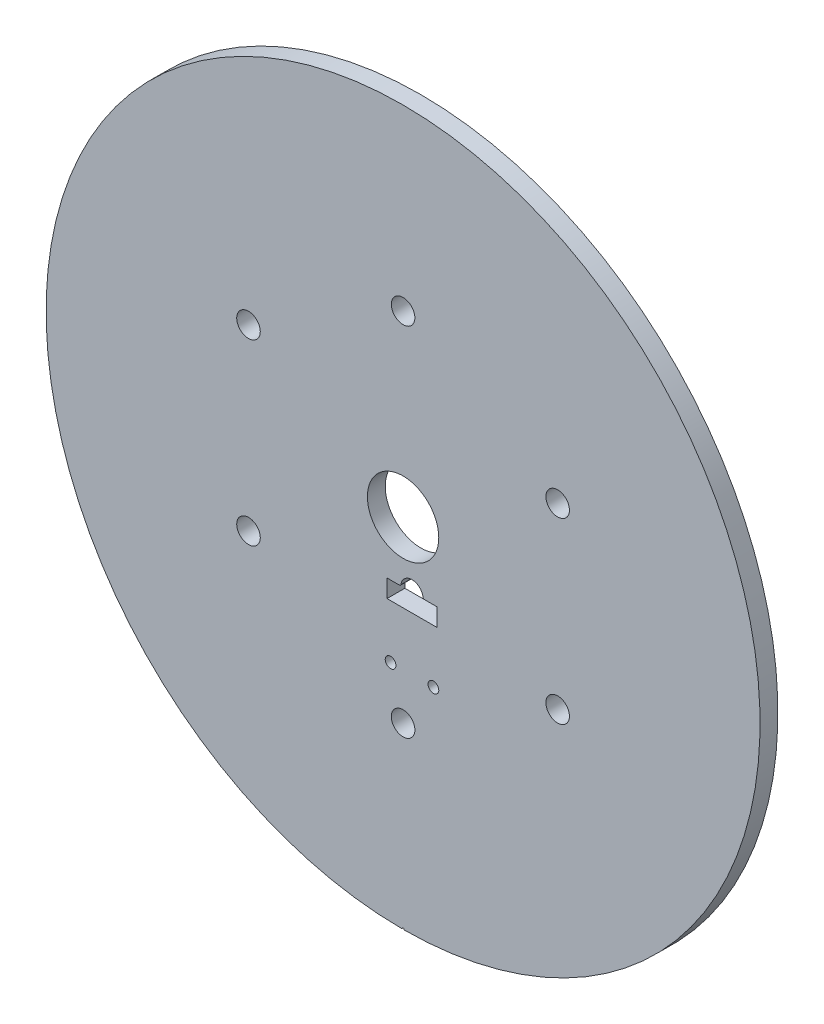
SolidWorks part; units mm, degrees
ref_plane "Front Plane" through (0, 0, 0) normal (0, 0, 1) x (1, 0, 0)
ref_plane "Top Plane" through (0, 0, 0) normal (0, 1, 0) x (1, 0, 0)
ref_plane "Right Plane" through (0, 0, 0) normal (1, 0, 0) x (0, 0, -1)
sketch "Sketch1" plane through (0, 0, 0) normal (0, 0, 1) x (1, 0, 0)
  circle A0 centre (0, 0) radius 100
  dimension "D1" = 200
extrude "Boss-Extrude1" add sketch "Sketch1" along normal blind 5
sketch "Sketch2" plane through (0, 0, 0) normal (0, 0, 1) x (1, 0, 0)
  line L0 (0, -2.75) -> (0, 2.75) construction
  line L1 (2.75, 0) -> (-2.75, 0) construction
  line L2 (-25, 30) -> (25, 30) construction
  line L3 (-25, 30) -> (-25, -30) construction
  line L4 (-25, -30) -> (25, -30) construction
  line L5 (25, 30) -> (25, -30) construction
  line L6 (-25, 30) -> (25, -30) construction
  line L7 (-25, -30) -> (25, 30) construction
  line L9 (-28.5, 30) -> (21.5, 30) construction
  line L10 (-28.5, 30) -> (-28.5, -30) construction
  line L11 (-28.5, -30) -> (21.5, -30) construction
  line L12 (21.5, 30) -> (21.5, -30) construction
  line L13 (-28.5, 30) -> (21.5, -30) construction
  line L14 (-28.5, -30) -> (21.5, 30) construction
  circle A0 centre (-3.5, 0) radius 3.175
  circle A1 centre (-3.5, -15) radius 2.5
  point P7 (0, 0)
  point P19 (-3.5, 0)
  dimension "D1" = 6.35
  dimension "D2" = 5
  dimension "D3" = 15
  dimension "D4" = 50
  dimension "D5" = 60
  dimension "D6" = 3.5
  dimension "D7" = 50
  dimension "D8" = 60
extrude "Cut-Extrude1" [suppressed] cut sketch "Sketch2" along normal through all
sketch "Sketch3" plane through (0, 0, 0) normal (1, 0, 0) x (0, 0, -1)
  line L0 (-46.5057, 0) -> (36.7778, 0) construction
sketch "Sketch4" plane through (0, 0, 0) normal (0, 0, 1) x (1, 0, 0)
  line L0 (0, -2.75) -> (0, 2.75) construction
  circle A0 centre (0, 50) radius 3
  dimension "D1" = 6
  dimension "D2" = 50
extrude "Cut-Extrude2" cut sketch "Sketch4" along normal through all
pattern_circular "CirPattern1" count 6 over 360 about axis through (0, 0, 0) along (0, 0, 1) of "Cut-Extrude2"
hole_wizard "M6 Clearance Hole1" positions "Sketch5" profile "Sketch6" hole size "M6" standard "ANSI Metric" end condition through all
sketch "Sketch5" plane through (0, 0, 5) normal (0, 0, 1) x (1, 0, 0)
  point P0 (0, 50)
  point P3 (43.3013, 25)
  point P6 (43.3013, -25)
  point P9 (0, -50)
  point P12 (-43.3013, -25)
  point P15 (-43.3013, 25)
sketch "Sketch6" plane through (0, 50, 5) normal (1, 0, 0) x (0, -1, 0)
  line L0 (0, 0) -> (0, 5)
  line L1 (0, 5) -> (3.3, 5)
  line L2 (3.3, 5) -> (3.3, 0)
  line L5 (3.3, 0) -> (0, 0)
  line L11 (0, -6.35) -> (0, 107.95) construction
  dimension "Thru Hole Dia." = 6.6
  dimension "Thru Hole Depth" = 5
sketch "Sketch7" plane through (0, 0, 0) normal (0, 0, 1) x (1, 0, 0)
  line L1 (9.5, -17) -> (-4.5, -17)
  line L2 (9.5, -17) -> (9.5, -22)
  line L3 (9.5, -22) -> (-4.5, -22)
  line L4 (-4.5, -17) -> (-4.5, -22)
  line L5 (9.5, -17) -> (-4.5, -22) construction
  line L6 (9.5, -22) -> (-4.5, -17) construction
  line L7 (9.5, 22) -> (-9.5, 22) construction
  line L8 (9.5, 22) -> (9.5, -22) construction
  line L9 (9.5, -22) -> (-9.5, -22) construction
  line L10 (-9.5, 22) -> (-9.5, -22) construction
  line L11 (9.5, 22) -> (-9.5, -22) construction
  line L12 (9.5, -22) -> (-9.5, 22) construction
  point P0 (2.5, -19.5)
  point P5 (0, 0)
  dimension "D2" = 14
  dimension "D3" = 5
  dimension "D4" = 19
  dimension "D5" = 44
extrude "Cut-Extrude3" cut sketch "Sketch7" along normal through all
sketch "Sketch8" plane through (0, 0, 0) normal (0, 0, -1) x (-1, 0, 0)
  line L0 (-2.5, -17) -> (-2.5, 46.2304) construction
  line L1 (-9.5, -17) -> (4.5, -17) construction
  line L3 (-9.5, -22) -> (9.5, -22) construction
  line L4 (-9.5, -22) -> (-9.5, 22) construction
  line L5 (-9.5, 22) -> (9.5, 22) construction
  line L6 (9.5, -22) -> (9.5, 22) construction
  circle A0 centre (-2.5, -10) radius 2.5 construction
  circle A1 centre (-2.5, 4) radius 1
  circle A2 centre (-2.5, 18) radius 0.5 construction
  circle A3 centre (-2.5, -10) radius 6 construction
  circle A4 centre (-2.5, 4) radius 6.35 construction
  circle A5 centre (-2.5, 18) radius 6 construction
  circle A6 centre (-2.5, -17) radius 3.1
  dimension "D5" = 12
  dimension "2" = 2
  dimension "D6" = 1
  dimension "D7" = 6.2
  dimension "6" = 5
  dimension "D4" = 12
  dimension "D1" = 19
  dimension "D2" = 44
  dimension "D3" = 14
  dimension "7" = 7
  dimension "D8" = 4
extrude "Cut-Extrude4" cut sketch "Sketch8" against normal through all
hole_wizard "#0000 Clearance Hole3" positions "Sketch9" profile "Sketch10" hole size "#0000" standard "ANSI Inch" end condition through all
sketch "Sketch9" plane through (0, 0, 0) normal (0, 0, -1) x (-1, 0, 0)
  circle A0 centre (0, 0) radius 100 construction
  point P4 (-2.5, 4)
  point P13 (-2.5, 4)
  point P15 (0, 0)
  point P18 (0, -100)
sketch "Sketch10" plane through (2.5, 4, 0) normal (1, 0, 0) x (0, 1, 0)
  line L0 (0, 0) -> (0, 5)
  line L1 (0, 5) -> (0.3302, 5)
  line L2 (0.3302, 5) -> (0.3302, 0)
  line L5 (0.3302, 0) -> (0, 0)
  line L11 (0, -6.35) -> (0, 107.95) construction
  dimension "Thru Hole Dia." = 0.6604
  dimension "Thru Hole Depth" = 5
hole_wizard "#39 (0.0995) Diameter Hole1" [suppressed] positions "Sketch16" profile "Sketch15" hole size "#39" standard "ANSI Inch"
sketch "Sketch16" plane through (0, 0, 0) normal (0, 0, -1) x (-1, 0, 0)
  point P0 (-2.5, 18)
sketch "Sketch15" plane through (2.5, 18, 0) normal (1, 0, 0) x (0, 1, 0)
  line L0 (0, 0) -> (0, 10)
  line L1 (0, 10) -> (1.2636, 10)
  line L2 (1.2636, 10) -> (1.2636, 0)
  line L5 (1.2636, 0) -> (0, 0)
  line L11 (0, -6.35) -> (0, 107.95) construction
  dimension "Thru Hole Dia." = 2.5273
  dimension "Thru Hole Depth" = 10
hole_wizard "M8x1.0 Tapped Hole1" [suppressed] positions "Sketch17" profile "Sketch18" tap size "M8x1.0" standard "ANSI Metric"
sketch "Sketch17" plane through (0, 0, 0) normal (0, 0, -1) x (-1, 0, 0)
  point P0 (-2.5, -10)
sketch "Sketch18" plane through (2.5, -10, 0) normal (1, 0, 0) x (0, 1, 0)
  line L0 (0, 0) -> (0, 21.103)
  line L1 (0, 21.103) -> (3.5, 19)
  line L2 (3.5, 19) -> (3.5, 0)
  line L5 (3.5, 0) -> (0, 0)
  line L10 (0, 21.103) -> (-3.5, 19) construction
  line L11 (0, -6.35) -> (0, 107.95) construction
  dimension "Tap Drill Dia." = 7
  dimension "Tap Drill Depth" = 19
  dimension "Drill Angle" = 118
cosmetic thread "Hole Thread1" [suppressed] parameters "D1"=16, "D2"=8
sketch "Sketch19" [suppressed] plane through (0, 0, 0) normal (0, 0, -1) x (-1, 0, 0)
  circle A0 centre (-2.5, -10) radius 5
  dimension "D1" = 10
extrude "Cut-Extrude5" [suppressed] cut sketch "Sketch19" against normal blind 3
fillet "Fillet1" radius 0.5 2 edges at (-0.6, -17, 2.5) (5.6, -17, 2.5)
sketch "Sketch20" plane through (0, 0, 0) normal (0, 0, -1) x (-1, 0, 0)
  line L0 (-2.5, -22) -> (-2.5, -42.4383) construction
  line L1 (4.5, -22) -> (-9.5, -22) construction
  circle A0 centre (-8.5, -37) radius 1.5
  circle A1 centre (3.5, -37) radius 1.5
  dimension "D1" = 3
  dimension "D2" = 6
  dimension "D3" = 15
extrude "Cut-Extrude6" cut sketch "Sketch20" against normal through all
sketch "Sketch21" plane through (0, 0, 0) normal (0, 0, 1) x (1, 0, 0)
  circle A0 centre (0, 0) radius 10
  dimension "D1" = 20
extrude "Cut-Extrude9" cut sketch "Sketch21" along normal through all
